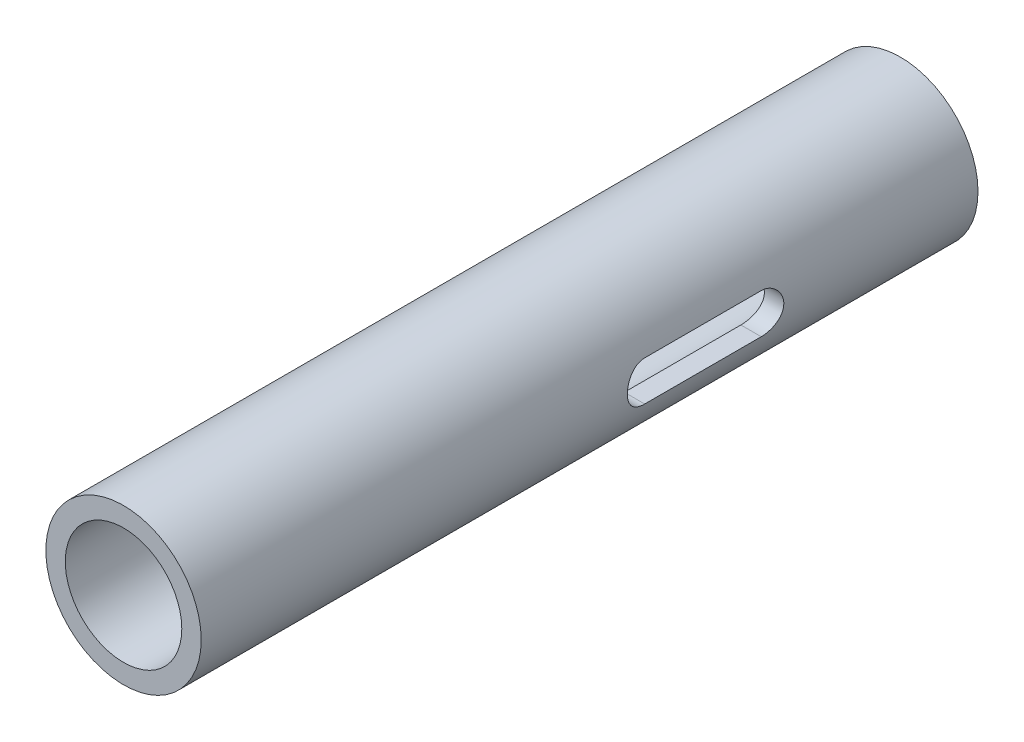
SolidWorks part; units mm, degrees
material "Delrin 2700 NC010, Low Viscosity Acetal Copolymer (SS)"
ref_plane "Front Plane" through (0, 0, 0) normal (0, 0, 1) x (1, 0, 0)
ref_plane "Top Plane" through (0, 0, 0) normal (0, 1, 0) x (1, 0, 0)
ref_plane "Right Plane" through (0, 0, 0) normal (1, 0, 0) x (0, 0, -1)
sketch "Sketch1" plane through (0, 0, 0) normal (0, 0, 1) x (1, 0, 0)
  circle A0 centre (0, 0) radius 12.7
  circle A1 centre (0, 0) radius 9.525
  dimension "D1" = 25.4
  dimension "D2" = 19.05
extrude "Boss-Extrude1" add sketch "Sketch1" along normal blind 127
sketch "Sketch2" plane through (0, 0, 0) normal (1, 0, 0) x (0, 0, -1)
  line L0 (-35.0139, 0) -> (-54.0639, 0) construction
  line L1 (-35.0139, -3.2639) -> (-54.0639, -3.2639)
  line L2 (-35.0139, 3.2639) -> (-54.0639, 3.2639)
  line L4 (0, -12.7) -> (0, 12.7) construction
  arc A0 (-35.0139, -3.2639) -> (-35.0139, 3.2639) centre (-35.0139, 0) ccw
  arc A1 (-54.0639, 3.2639) -> (-54.0639, -3.2639) centre (-54.0639, 0) ccw
  point P2 (-44.5389, 0)
  point P7 (-31.75, 0)
  dimension "D2" = 6.5278
  dimension "D1" = 19.05
  dimension "D3" = 31.75
extrude "Cut-Extrude1" cut sketch "Sketch2" against normal through all both and the other way through all
